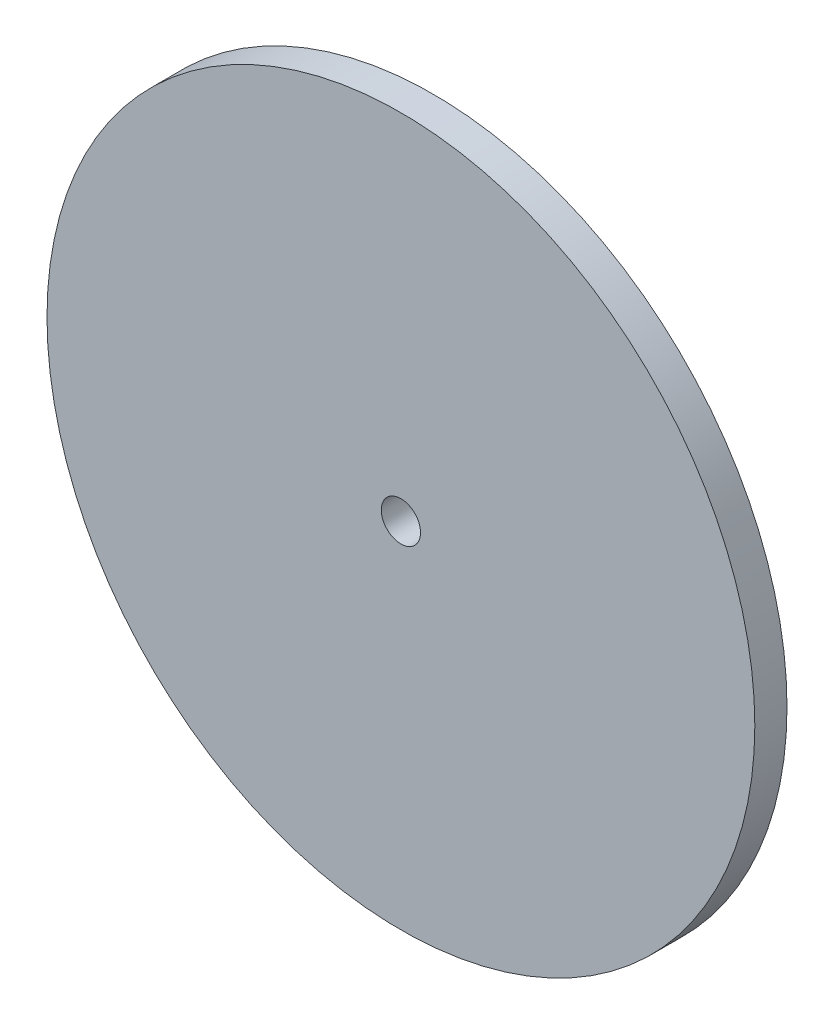
SolidWorks part; units mm, degrees
material "Balsa"
ref_plane "Front Plane" through (0, 0, 0) normal (0, 0, 1) x (1, 0, 0)
ref_plane "Top Plane" through (0, 0, 0) normal (0, 1, 0) x (1, 0, 0)
ref_plane "Right Plane" through (0, 0, 0) normal (1, 0, 0) x (0, 0, -1)
sketch "Sketch1" plane through (0, 0, 0) normal (0, 0, 1) x (1, 0, 0)
  circle A1 centre (0, 0) radius 55
  circle A2 centre (0, 0) radius 3.05
  dimension "D1" = 110
  dimension "D2" = 6.1
extrude "Boss-Extrude1" add sketch "Sketch1" along normal blind 5
